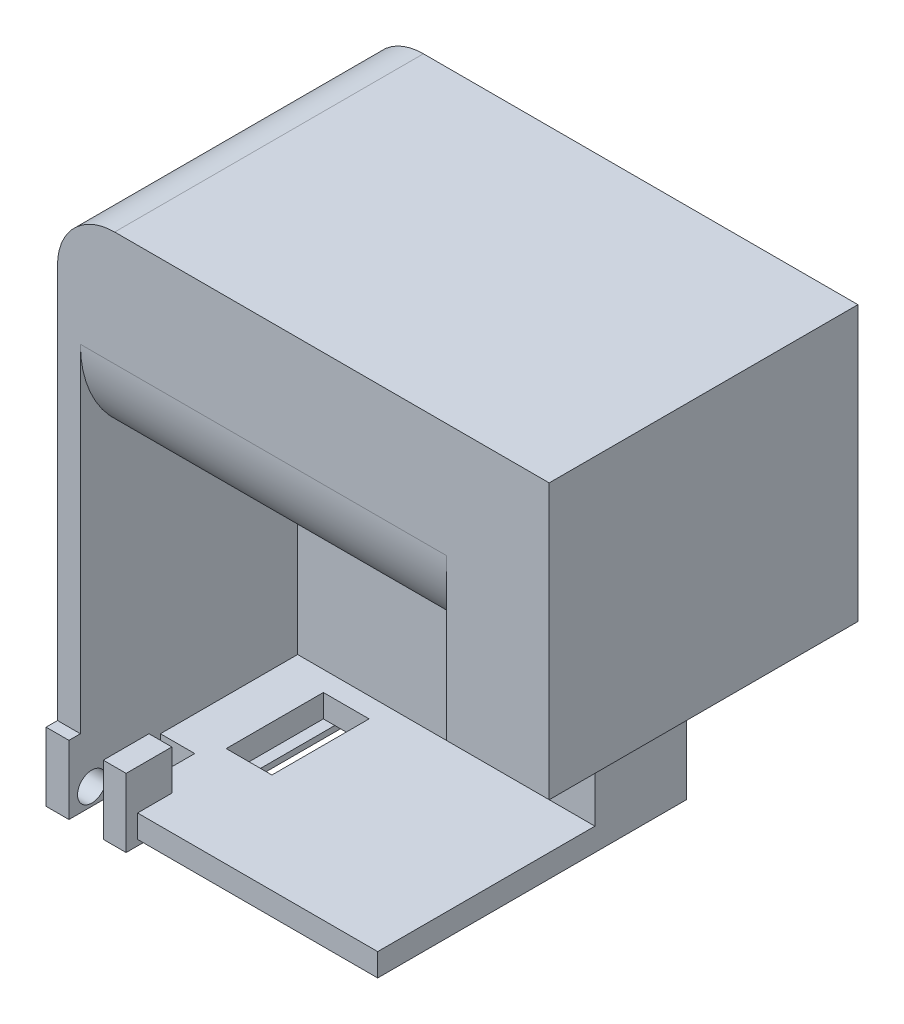
SolidWorks part; units mm, degrees
ref_plane "Front Plane" through (0, 0, 0) normal (0, 0, 1) x (1, 0, 0)
ref_plane "Top Plane" through (0, 0, 0) normal (0, 1, 0) x (1, 0, 0)
ref_plane "Right Plane" through (0, 0, 0) normal (1, 0, 0) x (0, 0, -1)
sketch "Sketch1" plane through (0, 0, 0) normal (0, 1, 0) x (1, 0, 0)
  line L1 (14, -11) -> (-14, -11)
  line L2 (14, -11) -> (14, 11)
  line L3 (14, 11) -> (-14, 11)
  line L4 (-14, -11) -> (-14, 11)
  line L5 (14, -11) -> (-14, 11) construction
  line L6 (14, 11) -> (-14, -11) construction
  point P0 (0, 0)
  dimension "D1" = 22
  dimension "D2" = 28
extrude "Boss-Extrude1" add sketch "Sketch1" along normal blind 32
sketch "Sketch21" plane through (0, 0, 11) normal (0, 0, 1) x (1, 0, 0)
  line L0 (14, 32) -> (14, 0) construction
  line L1 (-12, 25) -> (14, 25)
  line L2 (-12, 25) -> (-12, 2)
  line L3 (-12, 2) -> (14, 2)
  line L4 (14, 25) -> (14, 2)
  line L5 (-14, 32) -> (-14, 0) construction
  line L6 (-14, 0) -> (14, 0) construction
  dimension "D1" = 2
  dimension "D2" = 2
  dimension "D3" = 23
extrude "Cut-Extrude10" cut sketch "Sketch21" against normal blind 17
sketch "Sketch22" plane through (0, 2, 0) normal (0, 1, 0) x (1, 0, 0)
  line L0 (-12, 6) -> (-12, -11) construction
  line L1 (-8, -4.25) -> (-4, -4.25)
  line L2 (-8, -4.25) -> (-8, 4.25)
  line L3 (-8, 4.25) -> (-4, 4.25)
  line L4 (-4, -4.25) -> (-4, 4.25)
  line L5 (-12, 6) -> (14, 6) construction
  point P6 (-8, 0)
  dimension "D1" = 4
  dimension "D2" = 8
  dimension "D3" = 8.5
  dimension "D4" = 6
extrude "Cut-Extrude11" cut sketch "Sketch22" against normal through all
sketch "Sketch23" plane through (0, 0, -11) normal (0, 0, -1) x (-1, 0, 0)
  line L0 (-14, 32) -> (14, 32) construction
  line L1 (-5, 18.5) -> (5, 18.5)
  line L2 (-5, 18.5) -> (-5, 13.5)
  line L3 (-5, 13.5) -> (5, 13.5)
  line L4 (5, 18.5) -> (5, 13.5)
  line L5 (14, 32) -> (14, 0) construction
  point P4 (0, 18.5)
  point P7 (0, 32)
  point P8 (5, 16)
  point P11 (14, 16)
  dimension "D1" = 5
  dimension "D2" = 10
extrude "Cut-Extrude12" cut sketch "Sketch23" against normal up to surface (5 mm away) up to face at (1, 13.5, -6)
sketch "Sketch24" plane through (14, 0, 0) normal (1, 0, 0) x (0, 0, -1)
  line L1 (-13, 45) -> (13, 45)
  line L2 (-13, 45) -> (-13, 21)
  line L3 (-13, 21) -> (13, 21)
  line L4 (13, 45) -> (13, 21)
  line L5 (-11, 0) -> (11, 0) construction
  line L6 (-11, 32) -> (11, 32) construction
  point P6 (0, 45)
  point P9 (0, 32)
  dimension "D1" = 21
  dimension "D2" = 26
  dimension "D3" = 24
extrude "Boss-Extrude4" add sketch "Sketch24" along normal blind 15
sketch "Sketch25" plane through (14, 0, 0) normal (-1, 0, 0) x (0, 0, 1)
  line L0 (11, 32) -> (11, 25) construction
  line L1 (11, 32) -> (-11, 32) construction
  line L2 (-11, 32) -> (-11, 21) construction
  line L3 (11, 32) -> (11, 25)
  line L4 (13, 45) -> (-13, 45)
  line L5 (-13, 45) -> (-13, 21)
  line L6 (-13, 21) -> (13, 21)
  line L7 (13, 21) -> (13, 45)
  line L8 (13, 45) -> (-13, 45)
  line L9 (-13, 45) -> (-13, 21)
  line L10 (-13, 21) -> (-11, 21)
  line L11 (13, 25) -> (13, 45)
  line L12 (11, 32) -> (-11, 32)
  line L13 (-11, 32) -> (-11, 21)
  line L14 (11, 25) -> (13, 25)
  dimension "D1" = 0
extrude "Boss-Extrude5" add sketch "Sketch25" along normal up to surface (28 mm away) up to face at (-14, 16, 0)
sketch "Sketch26" plane through (0, 0, -11) normal (0, 0, -1) x (-1, 0, 0)
  line L0 (-5, 13.5) -> (5, 13.5) construction
  line L1 (5, 13.5) -> (5, 18.5) construction
  line L2 (5, 18.5) -> (-5, 18.5) construction
  line L3 (-5, 18.5) -> (-5, 13.5) construction
  line L4 (-5, 13.5) -> (5, 13.5)
  line L5 (5, 13.5) -> (5, 18.5)
  line L6 (5, 18.5) -> (-5, 18.5)
  line L7 (-5, 18.5) -> (-5, 13.5)
  line L8 (-14, 21) -> (-14, 0) construction
  line L9 (-14, 0) -> (14, 0) construction
  line L10 (14, 21) -> (14, 0) construction
  line L11 (14, 21) -> (-14, 21) construction
  line L12 (-14, 21) -> (-14, 0)
  line L13 (-14, 0) -> (14, 0)
  line L14 (14, 21) -> (14, 0)
  line L15 (14, 21) -> (-14, 21)
extrude "Boss-Extrude6" add sketch "Sketch26" along normal up to surface (2 mm away) up to face at (7.5, 33, -13)
sketch "Sketch27" plane through (0, 0, 11) normal (0, 0, 1) x (1, 0, 0)
  line L0 (-14, 25) -> (-14, 0) construction
  line L1 (14, 0) -> (-14, 0)
  line L2 (14, 0) -> (14, 2)
  line L3 (14, 2) -> (-12, 2)
  line L4 (-14, 0) -> (-14, 2)
  line L5 (-12, 2) -> (14, 2) construction
  line L6 (-14, 25) -> (-12, 25)
  line L7 (-14, 25) -> (-14, 2)
  line L9 (-12, 25) -> (-12, 2)
extrude "Boss-Extrude7" add sketch "Sketch27" along normal up to surface (2 mm away) up to face at (9.6667, 30.3333, 13)
fillet "Fillet1" radius 5 1 edges at (-14, 45, 0)
fillet "Fillet2" radius 10 1 edges at (1, 25, 13)
sketch "Sketch30" plane through (-14, 0, 0) normal (-1, 0, 0) x (0, 0, 1)
  line L0 (-13, 0) -> (13, 0) construction
  line L1 (-13, 0) -> (-13, 40) construction
  line L2 (13, 40) -> (13, 0) construction
  circle A0 centre (-12, 1) radius 1.25
  circle A1 centre (12, 1) radius 1.25
  point P4 (0, 0)
  point P9 (10.267, 1)
  point P10 (0, 0)
  dimension "D1" = 2.5
  dimension "D2" = 1
  dimension "D3" = 1
  dimension "D4" = 1
sketch "Sketch31" plane through (0, 0, 0) normal (0, -1, 0) x (1, 0, 0)
  line L0 (14, 13) -> (-14, 13) construction
  line L1 (-14, -13) -> (-12, -13)
  line L2 (-14, -13) -> (-14, 13)
  line L3 (-14, 13) -> (-12, 13)
  line L4 (-12, -13) -> (-12, 13)
  dimension "D1" = 2
extrude "Boss-Extrude8" add sketch "Sketch31" along normal blind 0.5
sketch "Sketch36" plane through (0, 0, 13) normal (0, 0, 1) x (1, 0, 0)
  line L0 (14, 0) -> (-12, 0) construction
  line L1 (-12, 2) -> (-7, 2)
  line L3 (-12, 0) -> (-7, 0)
  line L4 (-7, 2) -> (-7, 0)
  line L5 (-14, 40) -> (-14, -0.5) construction
  line L6 (-14, 5.5) -> (-12, 5.5)
  line L7 (-14, 5.5) -> (-14, -0.5)
  line L8 (-14, -0.5) -> (-12, -0.5)
  line L9 (-12, 5.5) -> (-12, 2)
  line L10 (-12, 0) -> (-12, -0.5)
  dimension "D1" = 6
  dimension "D2" = 5
extrude "Boss-Extrude12" add sketch "Sketch36" along normal blind 1 contours L6 L9 L1 L4 L3 L10 L8 L7
sketch "Sketch41" plane through (0, 2, 0) normal (0, 1, 0) x (1, 0, 0)
  line L1 (-7, -14) -> (-9, -14)
  line L2 (-7, -14) -> (-7, -10)
  line L3 (-7, -10) -> (-9, -10)
  line L4 (-9, -14) -> (-9, -10)
  dimension "D1" = 2
  dimension "D2" = 4
extrude "Boss-Extrude15" add sketch "Sketch41" along normal up to surface (3.5 mm away) up to face at (-13, 5.5, 13.5)
sketch "Sketch44" plane through (0, 0, -13) normal (0, 0, -1) x (-1, 0, 0)
  line L1 (14, -0.5) -> (7, -0.5)
  line L2 (14, -0.5) -> (14, 5.5)
  line L3 (14, 5.5) -> (7, 5.5)
  line L4 (7, -0.5) -> (7, 5.5)
  dimension "D1" = 6
  dimension "D2" = 7
extrude "Boss-Extrude17" add sketch "Sketch44" along normal blind 1
extrude "Cut-Extrude13" cut sketch "Sketch30" against normal blind 6
sketch "Sketch32" plane through (-12, 0, 0) normal (1, 0, 0) x (0, 0, -1)
  line L6 (13, 0) -> (12.75, 0)
  line L7 (11.25, 0) -> (-11.25, 0)
  line L8 (-12.75, 0) -> (-14, 0)
  line L9 (-14, 0) -> (-14, -0.5)
  line L10 (-14, -0.5) -> (13, -0.5)
  line L11 (13, -0.5) -> (13, 0)
  line L12 (13, 0) -> (12.75, 0)
  line L13 (11.25, 0) -> (-11.25, 0)
  line L14 (-12.75, 0) -> (-14, 0)
  line L16 (-14, -0.5) -> (13, -0.5)
  line L18 (-14, 0) -> (-14, -0.5)
  line L19 (13, -0.5) -> (13, 0)
  arc A2 (11.25, 0) -> (12.75, 0) centre (12, 1) ccw
  arc A3 (-12.75, 0) -> (-11.25, 0) centre (-12, 1) ccw
  arc A4 (11.25, 0) -> (12.75, 0) centre (12, 1) ccw
  arc A5 (-12.75, 0) -> (-11.25, 0) centre (-12, 1) ccw
  dimension "D1" = 0
extrude "Boss-Extrude9" add sketch "Sketch32" along normal up to surface (4 mm away) up to face at (-8, 1.125, 12)
sketch "Sketch37" plane through (0, 0, 0) normal (0, -1, 0) x (1, 0, 0)
  line L0 (-8, 14) -> (-7, 14) construction
  line L1 (-8, 14) -> (-7, 14)
  line L2 (-8, 14) -> (-8, -13)
  line L3 (-8, -13) -> (-7, -13)
  line L4 (-7, 14) -> (-7, -13)
  line L5 (-7, -13) -> (14, -13) construction
extrude "Boss-Extrude13" add sketch "Sketch37" along normal up to surface (0.5 mm away) up to face at (-9.6667, -0.5, -4.3333)
sketch "Sketch38" plane through (0, 0, 14) normal (0, 0, 1) x (1, 0, 0)
  line L0 (-14, -0.5) -> (-7, -0.5) construction
  line L1 (-12, 2) -> (-9, 2)
  line L2 (-12, 2) -> (-12, -0.5)
  line L3 (-12, -0.5) -> (-9, -0.5)
  line L4 (-9, 2) -> (-9, -0.5)
  dimension "D1" = 3
extrude "Cut-Extrude15" cut sketch "Sketch38" against normal blind 8
sketch "Sketch39" plane through (14, 0, 0) normal (-1, 0, 0) x (0, 0, 1)
  line L4 (13, 21) -> (13, 35)
  line L5 (3, 25) -> (-6, 25)
  line L6 (-6, 25) -> (-6, 21)
  line L7 (-6, 21) -> (13, 21)
  line L8 (13, 21) -> (13, 35)
  line L9 (3, 25) -> (-6, 25)
  line L10 (-6, 25) -> (-6, 21)
  line L11 (-6, 21) -> (13, 21)
  arc A1 (3, 25) -> (13, 35) centre (3, 35) ccw
  arc A2 (3, 25) -> (13, 35) centre (3, 35) ccw
  dimension "D1" = 0
extrude "Cut-Extrude16" cut sketch "Sketch39" against normal blind 6
sketch "Sketch45" plane through (0, 0, -14) normal (0, 0, -1) x (-1, 0, 0)
  line L0 (7, -0.5) -> (14, -0.5) construction
  line L1 (9, -0.5) -> (12, -0.5)
  line L2 (9, -0.5) -> (9, 5.5)
  line L3 (9, 5.5) -> (12, 5.5)
  line L4 (12, -0.5) -> (12, 5.5)
  line L5 (14, -0.5) -> (14, 5.5) construction
  line L6 (7, 5.5) -> (7, -0.5) construction
  dimension "D1" = 2
  dimension "D2" = 2
  dimension "D3" = 6
extrude "Cut-Extrude18" cut sketch "Sketch45" against normal blind 7
sketch "Sketch46" plane through (0, 0, -13) normal (0, 0, -1) x (-1, 0, 0)
  line L10 (7, 0) -> (7, 5.5)
  line L11 (7, 5.5) -> (9, 5.5)
  line L12 (9, 5.5) -> (12, 5.5)
  line L13 (12, 5.5) -> (14, 5.5)
  line L14 (14, 5.5) -> (14, 40)
  line L15 (9, 45) -> (-29, 45)
  line L16 (-29, 45) -> (-29, 21)
  line L17 (-29, 21) -> (-14, 21)
  line L18 (-14, 21) -> (-14, 0)
  line L19 (-14, 0) -> (7, 0)
  line L20 (7, 0) -> (7, 5.5)
  line L21 (7, 5.5) -> (9, 5.5)
  line L22 (9, 5.5) -> (12, 5.5)
  line L23 (12, 5.5) -> (14, 5.5)
  line L24 (14, 5.5) -> (14, 40)
  line L25 (9, 45) -> (-29, 45)
  line L26 (-29, 45) -> (-29, 21)
  line L27 (-29, 21) -> (-14, 21)
  line L28 (-14, 21) -> (-14, 0)
  line L29 (-14, 0) -> (7, 0)
  arc A1 (14, 40) -> (9, 45) centre (9, 40) ccw
  arc A2 (14, 40) -> (9, 45) centre (9, 40) ccw
  dimension "D1" = 0
extrude "Boss-Extrude18" add sketch "Sketch46" along normal up to surface (1 mm away) up to face at (-13, 2.5, -14)
sketch "Sketch48" plane through (0, 0, -13) normal (0, 0, 1) x (1, 0, 0)
  line L4 (-5, 18.5) -> (-5, 13.5)
  line L5 (-5, 13.5) -> (5, 13.5)
  line L6 (5, 13.5) -> (5, 18.5)
  line L7 (5, 18.5) -> (-5, 18.5)
  line L8 (-5, 18.5) -> (-5, 13.5)
  line L9 (-5, 13.5) -> (5, 13.5)
  line L10 (5, 13.5) -> (5, 18.5)
  line L11 (5, 18.5) -> (-5, 18.5)
  dimension "D1" = 0
extrude "Cut-Extrude19" cut sketch "Sketch48" against normal through all
